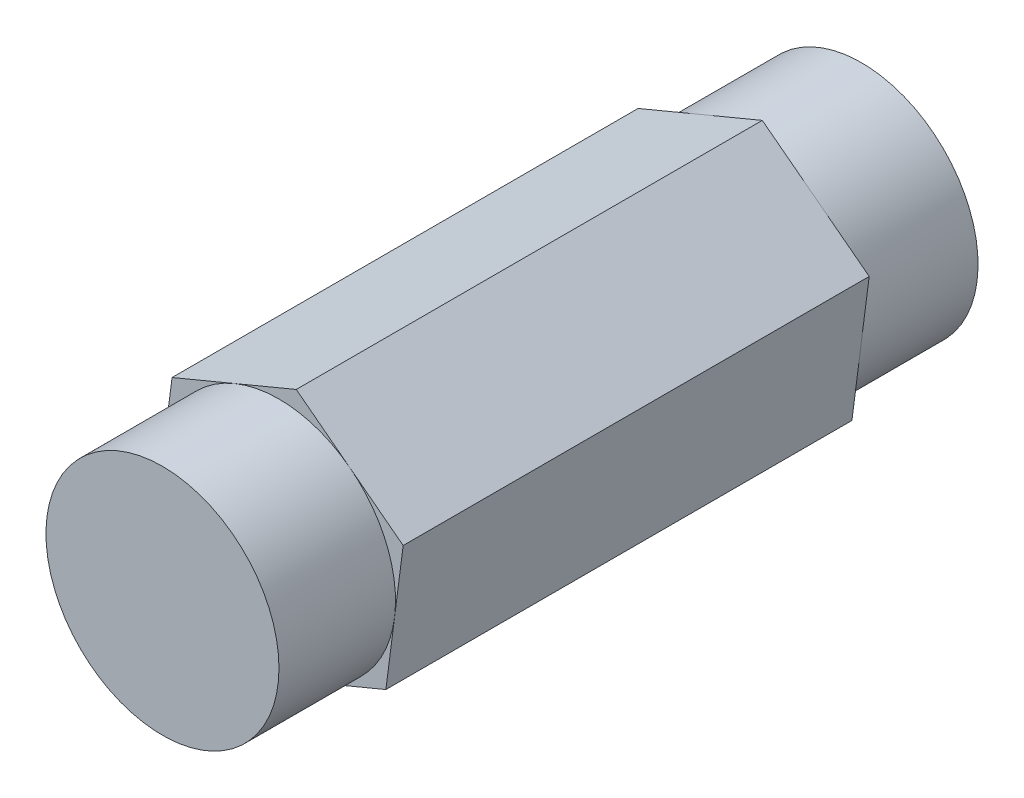
SolidWorks part; units mm, degrees
ref_plane "前视基准面" through (0, 0, 0) normal (0, 0, 1) x (1, 0, 0)
ref_plane "上视基准面" through (0, 0, 0) normal (0, 1, 0) x (1, 0, 0)
ref_plane "右视基准面" through (0, 0, 0) normal (1, 0, 0) x (0, 0, -1)
sketch "草图1" plane through (0, 0, 0) normal (0, 0, 1) x (1, 0, 0)
  line L1 (5.3294, 2.2206) -> (0.7416, 5.7257)
  line L2 (0.7416, 5.7257) -> (-4.5878, 3.5051)
  line L3 (-4.5878, 3.5051) -> (-5.3294, -2.2206)
  line L4 (-5.3294, -2.2206) -> (-0.7416, -5.7257)
  line L5 (-0.7416, -5.7257) -> (4.5878, -3.5051)
  line L6 (4.5878, -3.5051) -> (5.3294, 2.2206)
  circle A0 centre (0, 0) radius 5 construction
extrude "凸台-拉伸2" add sketch "草图1" along normal blind 20
sketch "草图2" plane through (0, 0, 0) normal (0, 0, -1) x (-1, 0, 0)
  circle A0 centre (0, 0) radius 5
extrude "凸台-拉伸3" add sketch "草图2" along normal blind 5
sketch "草图3" plane through (0, 0, 20) normal (0, 0, 1) x (1, 0, 0)
  circle A0 centre (0, 0) radius 5
extrude "凸台-拉伸4" add sketch "草图3" along normal blind 5
